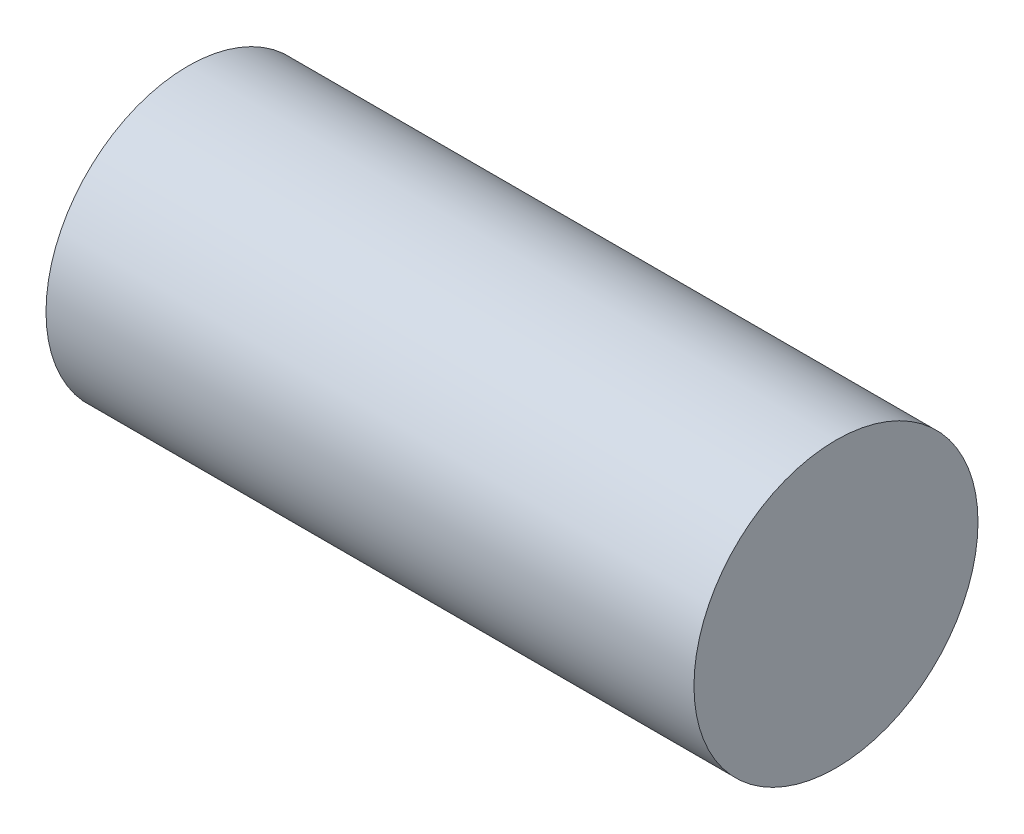
SolidWorks part; units mm, degrees
material "AISI 1045 Steel, cold drawn"
ref_plane "Front Plane" through (0, 0, 0) normal (0, 0, 1) x (1, 0, 0)
ref_plane "Top Plane" through (0, 0, 0) normal (0, 1, 0) x (1, 0, 0)
ref_plane "Right Plane" through (0, 0, 0) normal (1, 0, 0) x (0, 0, -1)
sketch "Sketch1" plane through (0, 0, 0) normal (1, 0, 0) x (0, 0, -1)
  circle A0 centre (0, 0) radius 38.1
  dimension "D1" = 76.2
extrude "Boss-Extrude1" add sketch "Sketch1" along normal blind 173.8376
